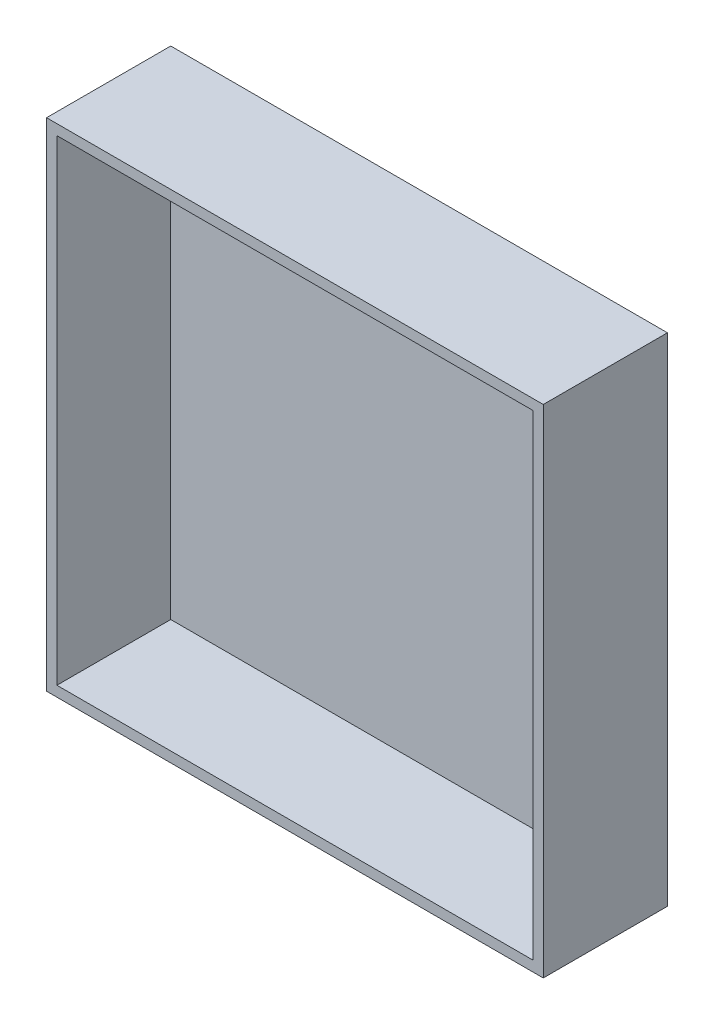
SolidWorks part; units mm, degrees
ref_plane "正面" through (0, 0, 0) normal (0, 0, 1) x (1, 0, 0)
ref_plane "平面" through (0, 0, 0) normal (0, 1, 0) x (1, 0, 0)
ref_plane "右側面" through (0, 0, 0) normal (1, 0, 0) x (0, 0, -1)
sketch "ｽｹｯﾁ1" plane through (0, 0, 0) normal (0, 0, 1) x (1, 0, 0)
  line L1 (0, 0) -> (240, 0)
  line L2 (0, 0) -> (0, -240)
  line L3 (0, -240) -> (240, -240)
  line L4 (240, 0) -> (240, -240)
  dimension "D1" = 240
  dimension "D2" = 240
extrude "ﾎﾞｽ - 押し出し1" add sketch "ｽｹｯﾁ1" along normal blind 60
sketch "ｽｹｯﾁ2" plane through (0, 0, 60) normal (0, 0, 1) x (1, 0, 0)
  line L14 (5, -5) -> (5, -235)
  line L15 (5, -235) -> (235, -235)
  line L16 (235, -235) -> (235, -5)
  line L17 (235, -5) -> (5, -5)
  line L18 (5, -5) -> (5, -235)
  line L19 (5, -235) -> (235, -235)
  line L20 (235, -235) -> (235, -5)
  line L21 (235, -5) -> (5, -5)
  dimension "D1" = 5
extrude "ｶｯﾄ - 押し出し1" cut sketch "ｽｹｯﾁ2" against normal blind 55
